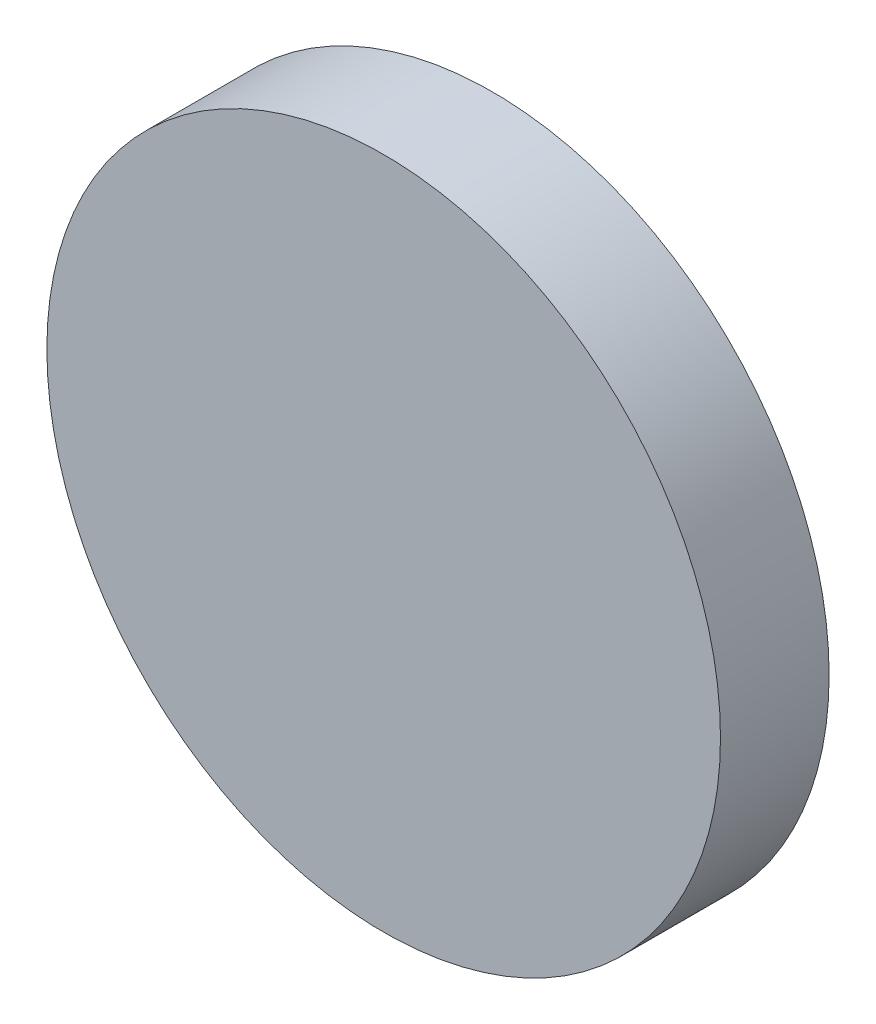
SolidWorks part; units mm, degrees
ref_plane "Front Plane" through (0, 0, 0) normal (0, 0, 1) x (1, 0, 0)
ref_plane "Top Plane" through (0, 0, 0) normal (0, 1, 0) x (1, 0, 0)
ref_plane "Right Plane" through (0, 0, 0) normal (1, 0, 0) x (0, 0, -1)
sketch "Sketch1" plane through (0, 0, 0) normal (0, 0, 1) x (1, 0, 0)
  circle A0 centre (0, 0) radius 15.5
  dimension "D1" = 31
extrude "Boss-Extrude1" add sketch "Sketch1" against normal blind 5
